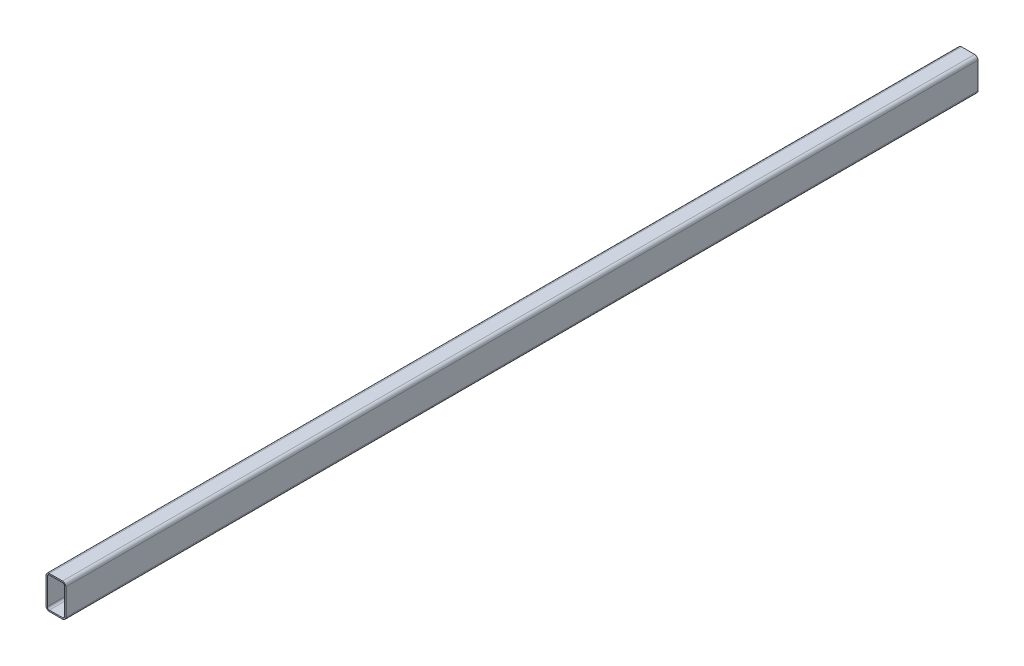
SolidWorks part; units mm, degrees
material "Plain Carbon Steel"
ref_plane "Front Plane" through (0, 0, 0) normal (0, 0, 1) x (1, 0, 0)
ref_plane "Top Plane" through (0, 0, 0) normal (0, 1, 0) x (1, 0, 0)
ref_plane "Right Plane" through (0, 0, 0) normal (1, 0, 0) x (0, 0, -1)
sketch "Sketch1" plane through (0, 0, 0) normal (0, 0, 1) x (1, 0, 0)
  line L0 (-47.3923, 0) -> (62.3765, 0) construction
  line L1 (0, 79.8651) -> (0, -80.6768) construction
  line L2 (-37.5, 0) -> (-37.5, -50)
  line L3 (-25, -62.5) -> (0, -62.5)
  line L4 (-32.5, 0) -> (-32.5, -50)
  line L5 (-25, -57.5) -> (0, -57.5)
  line L6 (-25, 57.5) -> (25, 57.5)
  line L7 (-32.5, 0) -> (-32.5, 50)
  line L8 (-25, 62.5) -> (25, 62.5)
  line L9 (-37.5, 0) -> (-37.5, 50)
  line L10 (25, -62.5) -> (0, -62.5)
  line L11 (37.5, 0) -> (37.5, -50)
  line L12 (37.5, 0) -> (37.5, 50)
  line L13 (25, -57.5) -> (0, -57.5)
  line L14 (32.5, 0) -> (32.5, -50)
  line L15 (32.5, 0) -> (32.5, 50)
  arc A0 (-37.5, -50) -> (-25, -62.5) centre (-25, -50) ccw
  arc A1 (-32.5, -50) -> (-25, -57.5) centre (-25, -50) ccw
  arc A2 (-32.5, 50) -> (-25, 57.5) centre (-25, 50) cw
  arc A3 (-37.5, 50) -> (-25, 62.5) centre (-25, 50) cw
  arc A4 (37.5, -50) -> (25, -62.5) centre (25, -50) cw
  arc A5 (37.5, 50) -> (25, 62.5) centre (25, 50) ccw
  arc A6 (32.5, -50) -> (25, -57.5) centre (25, -50) cw
  arc A7 (32.5, 50) -> (25, 57.5) centre (25, 50) ccw
  point P4 (-37.5, 62.5)
  point P10 (-37.5, -62.5)
  point P32 (0, 62.5)
  point P38 (0, 57.5)
  dimension "D3" = 12.5
  dimension "D1" = 62.5
  dimension "D2" = 37.5
  dimension "D4" = 5
extrude "Boss-Extrude1" add sketch "Sketch1" along normal mid plane 3450
